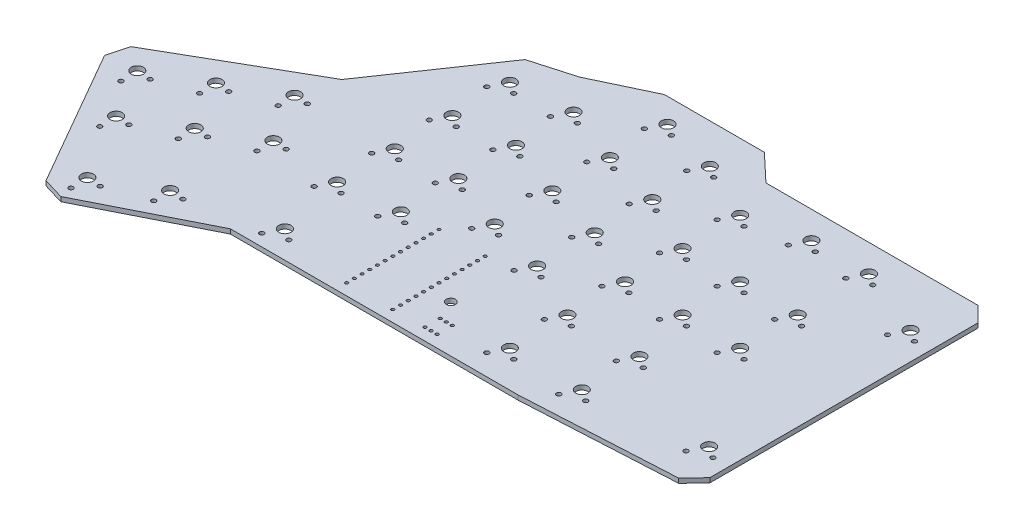
SolidWorks part; units mm, degrees
ref_plane "Front Plane" through (0, 0, 0) normal (0, 0, 1) x (1, 0, 0)
ref_plane "Top Plane" through (0, 0, 0) normal (0, 1, 0) x (1, 0, 0)
ref_plane "Right Plane" through (0, 0, 0) normal (1, 0, 0) x (0, 0, -1)
sketch "Main" plane through (0, 0, 0) normal (0, 1, 0) x (1, 0, 0)
  line L0 (6.46, 3.92) -> (12.81, 6.46) construction
  line L1 (0, 0) -> (18, 0) construction
  line L2 (0, 0) -> (0, 18) construction
  line L3 (0, 18) -> (18, 18) construction
  line L4 (18, 0) -> (18, 18) construction
  line L5 (2, 16) -> (16, 16)
  line L6 (2, 16) -> (2, 2)
  line L7 (2, 2) -> (16, 2)
  line L8 (16, 16) -> (16, 2)
  line L18 (9, 9) -> (6.46, 3.92) construction
  line L20 (9, 9) -> (12.81, 6.46) construction
  line L22 (25.46, 5.92) -> (31.81, 8.46) construction
  line L23 (19, 2) -> (37, 2) construction
  line L24 (19, 2) -> (19, 20) construction
  line L25 (19, 20) -> (37, 20) construction
  line L26 (37, 2) -> (37, 20) construction
  line L27 (21, 18) -> (35, 18)
  line L28 (21, 18) -> (21, 4)
  line L29 (21, 4) -> (35, 4)
  line L30 (35, 18) -> (35, 4)
  line L31 (28, 11) -> (25.46, 5.92) construction
  line L32 (28, 11) -> (31.81, 8.46) construction
  line L33 (44.46, 17.92) -> (50.81, 20.46) construction
  line L34 (38, 14) -> (56, 14) construction
  line L35 (38, 14) -> (38, 32) construction
  line L36 (38, 32) -> (56, 32) construction
  line L37 (56, 14) -> (56, 32) construction
  line L38 (40, 30) -> (54, 30)
  line L39 (40, 30) -> (40, 16)
  line L40 (40, 16) -> (54, 16)
  line L41 (54, 30) -> (54, 16)
  line L42 (47, 23) -> (44.46, 17.92) construction
  line L43 (47, 23) -> (50.81, 20.46) construction
  line L44 (63.46, 12.92) -> (69.81, 15.46) construction
  line L45 (57, 9) -> (75, 9) construction
  line L46 (57, 9) -> (57, 27) construction
  line L47 (57, 27) -> (75, 27) construction
  line L48 (75, 9) -> (75, 27) construction
  line L49 (59, 25) -> (73, 25)
  line L50 (59, 25) -> (59, 11)
  line L51 (59, 11) -> (73, 11)
  line L52 (73, 25) -> (73, 11)
  line L53 (66, 18) -> (63.46, 12.92) construction
  line L54 (66, 18) -> (69.81, 15.46) construction
  line L55 (82.46, 3.92) -> (88.81, 6.46) construction
  line L56 (76, 0) -> (94, 0) construction
  line L57 (76, 0) -> (76, 18) construction
  line L58 (76, 18) -> (94, 18) construction
  line L59 (94, 0) -> (94, 18) construction
  line L60 (78, 16) -> (92, 16)
  line L61 (78, 16) -> (78, 2)
  line L62 (78, 2) -> (92, 2)
  line L63 (92, 16) -> (92, 2)
  line L64 (85, 9) -> (82.46, 3.92) construction
  line L65 (85, 9) -> (88.81, 6.46) construction
  line L66 (101.46, -15.08) -> (107.81, -12.54) construction
  line L67 (95, -19) -> (113, -19) construction
  line L68 (95, -19) -> (95, -1) construction
  line L69 (95, -1) -> (113, -1) construction
  line L70 (113, -19) -> (113, -1) construction
  line L71 (97, -3) -> (111, -3)
  line L72 (97, -3) -> (97, -17)
  line L73 (97, -17) -> (111, -17)
  line L74 (111, -3) -> (111, -17)
  line L75 (104, -10) -> (101.46, -15.08) construction
  line L76 (104, -10) -> (107.81, -12.54) construction
  line L77 (120.46, -15.08) -> (126.81, -12.54) construction
  line L78 (114, -19) -> (132, -19) construction
  line L79 (114, -19) -> (114, -1) construction
  line L80 (114, -1) -> (132, -1) construction
  line L81 (132, -19) -> (132, -1) construction
  line L82 (116, -3) -> (130, -3)
  line L83 (116, -3) -> (116, -17)
  line L84 (116, -17) -> (130, -17)
  line L85 (130, -3) -> (130, -17)
  line L86 (123, -10) -> (120.46, -15.08) construction
  line L87 (123, -10) -> (126.81, -12.54) construction
  line L88 (2, -3) -> (16, -3)
  line L89 (2, -3) -> (2, -17)
  line L90 (2, -17) -> (16, -17)
  line L91 (16, -3) -> (16, -17)
  line L92 (21, -1) -> (35, -1)
  line L93 (21, -1) -> (21, -15)
  line L94 (21, -15) -> (35, -15)
  line L95 (35, -1) -> (35, -15)
  line L96 (40, 11) -> (54, 11)
  line L97 (40, 11) -> (40, -3)
  line L98 (40, -3) -> (54, -3)
  line L99 (54, 11) -> (54, -3)
  line L100 (59, 6) -> (73, 6)
  line L101 (59, 6) -> (59, -8)
  line L102 (59, -8) -> (73, -8)
  line L103 (73, 6) -> (73, -8)
  line L104 (78, -3) -> (92, -3)
  line L105 (78, -3) -> (78, -17)
  line L106 (78, -17) -> (92, -17)
  line L107 (92, -3) -> (92, -17)
  line L108 (97, -22) -> (111, -22)
  line L109 (97, -22) -> (97, -36)
  line L110 (97, -36) -> (111, -36)
  line L111 (111, -22) -> (111, -36)
  line L112 (116, -22) -> (130, -22)
  line L113 (116, -22) -> (116, -36)
  line L114 (116, -36) -> (130, -36)
  line L115 (130, -22) -> (130, -36)
  line L116 (6.46, -15.08) -> (12.81, -12.54) construction
  line L117 (0, -19) -> (18, -19) construction
  line L118 (0, -19) -> (0, -1) construction
  line L119 (0, -1) -> (18, -1) construction
  line L120 (18, -19) -> (18, -1) construction
  line L121 (9, -10) -> (6.46, -15.08) construction
  line L122 (9, -10) -> (12.81, -12.54) construction
  line L123 (25.46, -13.08) -> (31.81, -10.54) construction
  line L124 (19, -17) -> (37, -17) construction
  line L125 (19, -17) -> (19, 1) construction
  line L126 (19, 1) -> (37, 1) construction
  line L127 (37, -17) -> (37, 1) construction
  line L128 (28, -8) -> (25.46, -13.08) construction
  line L129 (28, -8) -> (31.81, -10.54) construction
  line L130 (44.46, -1.08) -> (50.81, 1.46) construction
  line L131 (38, -5) -> (56, -5) construction
  line L132 (38, -5) -> (38, 13) construction
  line L133 (38, 13) -> (56, 13) construction
  line L134 (56, -5) -> (56, 13) construction
  line L135 (47, 4) -> (44.46, -1.08) construction
  line L136 (47, 4) -> (50.81, 1.46) construction
  line L137 (63.46, -6.08) -> (69.81, -3.54) construction
  line L138 (57, -10) -> (75, -10) construction
  line L139 (57, -10) -> (57, 8) construction
  line L140 (57, 8) -> (75, 8) construction
  line L141 (75, -10) -> (75, 8) construction
  line L142 (66, -1) -> (63.46, -6.08) construction
  line L143 (66, -1) -> (69.81, -3.54) construction
  line L144 (82.46, -15.08) -> (88.81, -12.54) construction
  line L145 (76, -19) -> (94, -19) construction
  line L146 (76, -19) -> (76, -1) construction
  line L147 (76, -1) -> (94, -1) construction
  line L148 (94, -19) -> (94, -1) construction
  line L149 (85, -10) -> (82.46, -15.08) construction
  line L150 (85, -10) -> (88.81, -12.54) construction
  line L151 (101.46, -34.08) -> (107.81, -31.54) construction
  line L152 (95, -38) -> (113, -38) construction
  line L153 (95, -38) -> (95, -20) construction
  line L154 (95, -20) -> (113, -20) construction
  line L155 (113, -38) -> (113, -20) construction
  line L156 (104, -29) -> (101.46, -34.08) construction
  line L157 (104, -29) -> (107.81, -31.54) construction
  line L158 (120.46, -34.08) -> (126.81, -31.54) construction
  line L159 (114, -38) -> (132, -38) construction
  line L160 (114, -38) -> (114, -20) construction
  line L161 (114, -20) -> (132, -20) construction
  line L162 (132, -38) -> (132, -20) construction
  line L163 (123, -29) -> (120.46, -34.08) construction
  line L164 (123, -29) -> (126.81, -31.54) construction
  line L165 (2, -22) -> (16, -22)
  line L166 (2, -22) -> (2, -36)
  line L167 (2, -36) -> (16, -36)
  line L168 (16, -22) -> (16, -36)
  line L169 (21, -20) -> (35, -20)
  line L170 (21, -20) -> (21, -34)
  line L171 (21, -34) -> (35, -34)
  line L172 (35, -20) -> (35, -34)
  line L173 (40, -8) -> (54, -8)
  line L174 (40, -8) -> (40, -22)
  line L175 (40, -22) -> (54, -22)
  line L176 (54, -8) -> (54, -22)
  line L177 (59, -13) -> (73, -13)
  line L178 (59, -13) -> (59, -27)
  line L179 (59, -27) -> (73, -27)
  line L180 (73, -13) -> (73, -27)
  line L181 (78, -22) -> (92, -22)
  line L182 (78, -22) -> (78, -36)
  line L183 (78, -36) -> (92, -36)
  line L184 (92, -22) -> (92, -36)
  line L193 (6.46, -34.08) -> (12.81, -31.54) construction
  line L194 (0, -38) -> (18, -38) construction
  line L195 (0, -38) -> (0, -20) construction
  line L196 (0, -20) -> (18, -20) construction
  line L197 (18, -38) -> (18, -20) construction
  line L198 (9, -29) -> (6.46, -34.08) construction
  line L199 (9, -29) -> (12.81, -31.54) construction
  line L200 (25.46, -32.08) -> (31.81, -29.54) construction
  line L201 (19, -36) -> (37, -36) construction
  line L202 (19, -36) -> (19, -18) construction
  line L203 (19, -18) -> (37, -18) construction
  line L204 (37, -36) -> (37, -18) construction
  line L205 (28, -27) -> (25.46, -32.08) construction
  line L206 (28, -27) -> (31.81, -29.54) construction
  line L207 (44.46, -20.08) -> (50.81, -17.54) construction
  line L208 (38, -24) -> (56, -24) construction
  line L209 (38, -24) -> (38, -6) construction
  line L210 (38, -6) -> (56, -6) construction
  line L211 (56, -24) -> (56, -6) construction
  line L212 (47, -15) -> (44.46, -20.08) construction
  line L213 (47, -15) -> (50.81, -17.54) construction
  line L214 (63.46, -25.08) -> (69.81, -22.54) construction
  line L215 (57, -29) -> (75, -29) construction
  line L216 (57, -29) -> (57, -11) construction
  line L217 (57, -11) -> (75, -11) construction
  line L218 (75, -29) -> (75, -11) construction
  line L219 (66, -20) -> (63.46, -25.08) construction
  line L220 (66, -20) -> (69.81, -22.54) construction
  line L221 (82.46, -34.08) -> (88.81, -31.54) construction
  line L222 (76, -38) -> (94, -38) construction
  line L223 (76, -38) -> (76, -20) construction
  line L224 (76, -20) -> (94, -20) construction
  line L225 (94, -38) -> (94, -20) construction
  line L226 (85, -29) -> (82.46, -34.08) construction
  line L227 (85, -29) -> (88.81, -31.54) construction
  line L228 (97, 20.5) -> (111, 20.5)
  line L231 (97, 20.5) -> (97, 6.5)
  line L232 (97, 6.5) -> (111, 6.5)
  line L233 (111, 20.5) -> (111, 6.5)
  line L234 (116, 20.5) -> (130, 20.5)
  line L235 (116, 20.5) -> (116, 6.5)
  line L236 (116, 6.5) -> (130, 6.5)
  line L237 (130, 20.5) -> (130, 6.5)
  line L238 (101.46, 8.42) -> (107.81, 10.96) construction
  line L239 (95, 4.5) -> (113, 4.5) construction
  line L240 (95, 4.5) -> (95, 22.5) construction
  line L241 (95, 22.5) -> (113, 22.5) construction
  line L242 (2, -41) -> (16, -41)
  line L243 (2, -41) -> (2, -55)
  line L244 (2, -55) -> (16, -55)
  line L245 (16, -41) -> (16, -55)
  line L246 (21, -39) -> (35, -39)
  line L247 (21, -39) -> (21, -53)
  line L248 (21, -53) -> (35, -53)
  line L249 (35, -39) -> (35, -53)
  line L250 (40, -27) -> (54, -27)
  line L251 (40, -27) -> (40, -41)
  line L252 (40, -41) -> (54, -41)
  line L253 (54, -27) -> (54, -41)
  line L254 (59, -32) -> (73, -32)
  line L255 (59, -32) -> (59, -46)
  line L256 (59, -46) -> (73, -46)
  line L257 (73, -32) -> (73, -46)
  line L258 (78, -41) -> (92, -41)
  line L259 (78, -41) -> (78, -55)
  line L260 (78, -55) -> (92, -55)
  line L261 (92, -41) -> (92, -55)
  line L270 (6.46, -53.08) -> (12.81, -50.54) construction
  line L271 (0, -57) -> (18, -57) construction
  line L272 (0, -57) -> (0, -39) construction
  line L273 (0, -39) -> (18, -39) construction
  line L274 (18, -57) -> (18, -39) construction
  line L275 (9, -48) -> (6.46, -53.08) construction
  line L276 (9, -48) -> (12.81, -50.54) construction
  line L277 (25.46, -51.08) -> (31.81, -48.54) construction
  line L278 (19, -55) -> (37, -55) construction
  line L279 (19, -55) -> (19, -37) construction
  line L280 (19, -37) -> (37, -37) construction
  line L281 (37, -55) -> (37, -37) construction
  line L282 (28, -46) -> (25.46, -51.08) construction
  line L283 (28, -46) -> (31.81, -48.54) construction
  line L284 (44.46, -39.08) -> (50.81, -36.54) construction
  line L285 (38, -43) -> (56, -43) construction
  line L286 (38, -43) -> (38, -25) construction
  line L287 (38, -25) -> (56, -25) construction
  line L288 (56, -43) -> (56, -25) construction
  line L289 (47, -34) -> (44.46, -39.08) construction
  line L290 (47, -34) -> (50.81, -36.54) construction
  line L291 (63.46, -44.08) -> (69.81, -41.54) construction
  line L292 (57, -48) -> (75, -48) construction
  line L293 (57, -48) -> (57, -30) construction
  line L294 (57, -30) -> (75, -30) construction
  line L295 (75, -48) -> (75, -30) construction
  line L296 (66, -39) -> (63.46, -44.08) construction
  line L297 (66, -39) -> (69.81, -41.54) construction
  line L298 (82.46, -53.08) -> (88.81, -50.54) construction
  line L299 (76, -57) -> (94, -57) construction
  line L300 (76, -57) -> (76, -39) construction
  line L301 (76, -39) -> (94, -39) construction
  line L302 (94, -57) -> (94, -39) construction
  line L303 (85, -48) -> (82.46, -53.08) construction
  line L304 (85, -48) -> (88.81, -50.54) construction
  line L305 (113, 4.5) -> (113, 22.5) construction
  line L306 (104, 13.5) -> (101.46, 8.42) construction
  line L307 (104, 13.5) -> (107.81, 10.96) construction
  line L308 (120.46, 8.42) -> (126.81, 10.96) construction
  line L309 (114, 4.5) -> (132, 4.5) construction
  line L310 (114, 4.5) -> (114, 22.5) construction
  line L311 (114, 22.5) -> (132, 22.5) construction
  line L312 (132, 4.5) -> (132, 22.5) construction
  line L313 (123, 13.5) -> (120.46, 8.42) construction
  line L314 (123, 13.5) -> (126.81, 10.96) construction
  line L319 (97, -60) -> (111, -60)
  line L320 (97, -60) -> (97, -74)
  line L321 (97, -74) -> (111, -74)
  line L322 (111, -60) -> (111, -74)
  line L323 (116, -60) -> (130, -60)
  line L324 (116, -60) -> (116, -74)
  line L325 (116, -74) -> (130, -74)
  line L326 (130, -60) -> (130, -74)
  line L327 (101.46, -72.08) -> (107.81, -69.54) construction
  line L328 (95, -76) -> (113, -76) construction
  line L329 (95, -76) -> (95, -58) construction
  line L330 (95, -58) -> (113, -58) construction
  line L331 (113, -76) -> (113, -58) construction
  line L332 (104, -67) -> (101.46, -72.08) construction
  line L333 (104, -67) -> (107.81, -69.54) construction
  line L334 (120.46, -72.08) -> (126.81, -69.54) construction
  line L335 (114, -76) -> (132, -76) construction
  line L336 (114, -76) -> (114, -58) construction
  line L337 (114, -58) -> (132, -58) construction
  line L338 (132, -76) -> (132, -58) construction
  line L339 (123, -67) -> (120.46, -72.08) construction
  line L340 (123, -67) -> (126.81, -69.54) construction
  line L341 (97, -41) -> (111, -41)
  line L342 (97, -41) -> (97, -55)
  line L343 (97, -55) -> (111, -55)
  line L344 (111, -41) -> (111, -55)
  line L345 (116, -41) -> (130, -41)
  line L346 (116, -41) -> (116, -55)
  line L347 (116, -55) -> (130, -55)
  line L348 (130, -41) -> (130, -55)
  line L349 (101.46, -53.08) -> (107.81, -50.54) construction
  line L350 (95, -39) -> (113, -39) construction
  line L351 (113, -57) -> (113, -39) construction
  line L352 (104, -48) -> (101.46, -53.08) construction
  line L353 (104, -48) -> (107.81, -50.54) construction
  line L354 (120.46, -53.08) -> (126.81, -50.54) construction
  line L355 (114, -57) -> (132, -57) construction
  line L356 (114, -57) -> (114, -39) construction
  line L357 (114, -39) -> (132, -39) construction
  line L358 (132, -57) -> (132, -39) construction
  line L359 (123, -48) -> (120.46, -53.08) construction
  line L360 (123, -48) -> (126.81, -50.54) construction
  line L361 (95, -57) -> (113, -57) construction
  line L362 (95, -57) -> (95, -39) construction
  circle A0 centre (9, 9) radius 2 construction
  circle A1 centre (6.46, 3.92) radius 1.5 construction
  circle A2 centre (12.81, 6.46) radius 1.5 construction
  circle A6 centre (28, 11) radius 2 construction
  circle A7 centre (25.46, 5.92) radius 1.5 construction
  circle A8 centre (31.81, 8.46) radius 1.5 construction
  circle A9 centre (47, 23) radius 2 construction
  circle A10 centre (44.46, 17.92) radius 1.5 construction
  circle A11 centre (50.81, 20.46) radius 1.5 construction
  circle A12 centre (66, 18) radius 2 construction
  circle A13 centre (63.46, 12.92) radius 1.5 construction
  circle A14 centre (69.81, 15.46) radius 1.5 construction
  circle A15 centre (85, 9) radius 2 construction
  circle A16 centre (82.46, 3.92) radius 1.5 construction
  circle A17 centre (88.81, 6.46) radius 1.5 construction
  circle A18 centre (104, -10) radius 2 construction
  circle A19 centre (101.46, -15.08) radius 1.5 construction
  circle A20 centre (107.81, -12.54) radius 1.5 construction
  circle A21 centre (123, -10) radius 2 construction
  circle A22 centre (120.46, -15.08) radius 1.5 construction
  circle A23 centre (126.81, -12.54) radius 1.5 construction
  circle A24 centre (9, -10) radius 2 construction
  circle A25 centre (6.46, -15.08) radius 1.5 construction
  circle A26 centre (12.81, -12.54) radius 1.5 construction
  circle A27 centre (28, -8) radius 2 construction
  circle A28 centre (25.46, -13.08) radius 1.5 construction
  circle A29 centre (31.81, -10.54) radius 1.5 construction
  circle A30 centre (47, 4) radius 2 construction
  circle A31 centre (44.46, -1.08) radius 1.5 construction
  circle A32 centre (50.81, 1.46) radius 1.5 construction
  circle A33 centre (66, -1) radius 2 construction
  circle A34 centre (63.46, -6.08) radius 1.5 construction
  circle A35 centre (69.81, -3.54) radius 1.5 construction
  circle A36 centre (85, -10) radius 2 construction
  circle A37 centre (82.46, -15.08) radius 1.5 construction
  circle A38 centre (88.81, -12.54) radius 1.5 construction
  circle A39 centre (104, -29) radius 2 construction
  circle A40 centre (101.46, -34.08) radius 1.5 construction
  circle A41 centre (107.81, -31.54) radius 1.5 construction
  circle A42 centre (123, -29) radius 2 construction
  circle A43 centre (120.46, -34.08) radius 1.5 construction
  circle A44 centre (126.81, -31.54) radius 1.5 construction
  circle A45 centre (9, -29) radius 2 construction
  circle A46 centre (6.46, -34.08) radius 1.5 construction
  circle A47 centre (12.81, -31.54) radius 1.5 construction
  circle A48 centre (28, -27) radius 2 construction
  circle A49 centre (25.46, -32.08) radius 1.5 construction
  circle A50 centre (31.81, -29.54) radius 1.5 construction
  circle A51 centre (47, -15) radius 2 construction
  circle A52 centre (44.46, -20.08) radius 1.5 construction
  circle A53 centre (50.81, -17.54) radius 1.5 construction
  circle A54 centre (66, -20) radius 2 construction
  circle A55 centre (63.46, -25.08) radius 1.5 construction
  circle A56 centre (69.81, -22.54) radius 1.5 construction
  circle A57 centre (85, -29) radius 2 construction
  circle A58 centre (82.46, -34.08) radius 1.5 construction
  circle A59 centre (88.81, -31.54) radius 1.5 construction
  circle A60 centre (104, 13.5) radius 2 construction
  circle A61 centre (101.46, 8.42) radius 1.5 construction
  circle A62 centre (107.81, 10.96) radius 1.5 construction
  circle A63 centre (123, 13.5) radius 2 construction
  circle A64 centre (120.46, 8.42) radius 1.5 construction
  circle A65 centre (126.81, 10.96) radius 1.5 construction
  circle A66 centre (9, -48) radius 2 construction
  circle A67 centre (6.46, -53.08) radius 1.5 construction
  circle A68 centre (12.81, -50.54) radius 1.5 construction
  circle A69 centre (28, -46) radius 2 construction
  circle A70 centre (25.46, -51.08) radius 1.5 construction
  circle A71 centre (31.81, -48.54) radius 1.5 construction
  circle A72 centre (47, -34) radius 2 construction
  circle A73 centre (44.46, -39.08) radius 1.5 construction
  circle A74 centre (50.81, -36.54) radius 1.5 construction
  circle A75 centre (66, -39) radius 2 construction
  circle A76 centre (63.46, -44.08) radius 1.5 construction
  circle A77 centre (69.81, -41.54) radius 1.5 construction
  circle A78 centre (85, -48) radius 2 construction
  circle A79 centre (82.46, -53.08) radius 1.5 construction
  circle A80 centre (88.81, -50.54) radius 1.5 construction
  circle A87 centre (104, -67) radius 2 construction
  circle A88 centre (101.46, -72.08) radius 1.5 construction
  circle A89 centre (107.81, -69.54) radius 1.5 construction
  circle A90 centre (123, -67) radius 2 construction
  circle A91 centre (120.46, -72.08) radius 1.5 construction
  circle A92 centre (126.81, -69.54) radius 1.5 construction
  circle A93 centre (104, -48) radius 2 construction
  circle A94 centre (101.46, -53.08) radius 1.5 construction
  circle A95 centre (107.81, -50.54) radius 1.5 construction
  circle A96 centre (123, -48) radius 2 construction
  circle A97 centre (120.46, -53.08) radius 1.5 construction
  circle A98 centre (126.81, -50.54) radius 1.5 construction
  point P9 (9, 16)
  point P10 (9, 18)
  point P11 (2, 9)
  point P12 (0, 9)
  point P30 (28, 18)
  point P31 (28, 20)
  point P32 (21, 11)
  point P33 (19, 11)
  point P46 (47, 30)
  point P47 (47, 32)
  point P48 (40, 23)
  point P49 (38, 23)
  point P64 (66, 25)
  point P65 (66, 27)
  point P66 (59, 18)
  point P67 (57, 18)
  point P82 (85, 16)
  point P83 (85, 18)
  point P84 (78, 9)
  point P85 (76, 9)
  point P100 (104, -3)
  point P101 (104, -1)
  point P102 (97, -10)
  point P103 (95, -10)
  point P118 (123, -3)
  point P119 (123, -1)
  point P120 (116, -10)
  point P121 (114, -10)
  dimension "D6" = 4
  dimension "D7" = 3
  dimension "D10" = 1
  dimension "D11" = 5
  dimension "D1" = 18
  dimension "D2" = 14
  dimension "D3" = 3.81
  dimension "D4" = 2.54
  dimension "D5" = 2.54
  dimension "D8" = 1
  dimension "D9" = 12
  dimension "D12" = 1
  dimension "D13" = 2
  dimension "D14" = 1
  dimension "D15" = 9
  dimension "D16" = 1
  dimension "D17" = 5.08
  dimension "D18" = 1
  dimension "D20" = 1
  dimension "D22" = 4.5
  dimension "D23" = 2.54
  dimension "D24" = 2.54
  dimension "D25" = 2.54
  dimension "D26" = 2.54
  dimension "D27" = 2.54
  dimension "D28" = 2.54
  dimension "D19" = 4
  dimension "D21" = 2
sketch "EntBckSp" plane through (0, 0, 0) normal (0, 1, 0) x (1, 0, 0)
  line L0 (0, 0) -> (18, 0) construction
  line L1 (139, 11.25) -> (153, 11.25)
  line L2 (139, 11.25) -> (139, -2.75)
  line L3 (139, -2.75) -> (153, -2.75)
  line L4 (153, 11.25) -> (153, -2.75)
  line L5 (137, 18) -> (155, 18) construction
  line L6 (137, 18) -> (137, -9.5) construction
  line L7 (137, -9.5) -> (155, -9.5) construction
  line L8 (155, 18) -> (155, -9.5) construction
  line L9 (2, 2) -> (16, 2) construction
  line L10 (143.46, -0.83) -> (146, 4.25) construction
  line L11 (146, 4.25) -> (149.81, 1.71) construction
  line L12 (149.81, 1.71) -> (143.46, -0.83) construction
  line L13 (6.46, 3.92) -> (12.81, 6.46) construction
  line L14 (9, 9) -> (6.46, 3.92) construction
  line L15 (9, 9) -> (12.81, 6.46) construction
  line L16 (2, -55) -> (16, -55) construction
  line L17 (132, -19) -> (132, -1) construction
  line L18 (101.75, -41) -> (115.75, -41)
  line L19 (101.75, -41) -> (101.75, -55)
  line L20 (101.75, -55) -> (115.75, -55)
  line L21 (115.75, -41) -> (115.75, -55)
  line L22 (95, -39) -> (122.5, -39) construction
  line L23 (95, -39) -> (95, -57) construction
  line L24 (95, -57) -> (122.5, -57) construction
  line L25 (122.5, -39) -> (122.5, -57) construction
  line L26 (106.21, -53.08) -> (108.75, -48) construction
  line L27 (108.75, -48) -> (112.56, -50.54) construction
  line L28 (112.56, -50.54) -> (106.21, -53.08) construction
  line L29 (0, 18) -> (18, 18) construction
  line L30 (46.5, -79) -> (28.5, -79) construction
  line L31 (101.75, -60) -> (115.75, -60)
  line L32 (101.75, -60) -> (101.75, -74)
  line L33 (101.75, -74) -> (115.75, -74)
  line L34 (115.75, -60) -> (115.75, -74)
  line L35 (95, -58) -> (122.5, -58) construction
  line L36 (95, -58) -> (95, -76) construction
  line L37 (95, -76) -> (122.5, -76) construction
  line L38 (122.5, -58) -> (122.5, -76) construction
  line L39 (106.21, -72.08) -> (108.75, -67) construction
  line L40 (108.75, -67) -> (112.56, -69.54) construction
  line L41 (112.56, -69.54) -> (106.21, -72.08) construction
  line L42 (139, -55.25) -> (153, -55.25)
  line L43 (139, -55.25) -> (139, -69.25)
  line L44 (139, -69.25) -> (153, -69.25)
  line L45 (153, -55.25) -> (153, -69.25)
  line L46 (137, -48.5) -> (155, -48.5) construction
  line L47 (137, -48.5) -> (137, -76) construction
  line L48 (137, -76) -> (155, -76) construction
  line L49 (155, -48.5) -> (155, -76) construction
  line L50 (143.46, -67.33) -> (146, -62.25) construction
  line L51 (146, -62.25) -> (149.81, -64.79) construction
  line L52 (149.81, -64.79) -> (143.46, -67.33) construction
  line L64 (95, -38) -> (95, -20) construction
  line L65 (114, -38) -> (132, -38) construction
  line L66 (6.75, -63) -> (20.75, -63)
  line L67 (6.75, -63) -> (6.75, -77)
  line L68 (6.75, -77) -> (20.75, -77)
  line L69 (20.75, -63) -> (20.75, -77)
  line L70 (0, -61) -> (27.5, -61) construction
  line L71 (0, -61) -> (0, -79) construction
  line L72 (0, -79) -> (27.5, -79) construction
  line L73 (27.5, -61) -> (27.5, -79) construction
  line L74 (11.21, -75.08) -> (13.75, -70) construction
  line L75 (13.75, -70) -> (17.56, -72.54) construction
  line L76 (17.56, -72.54) -> (11.21, -75.08) construction
  line L77 (94, -76) -> (76, -76) construction
  line L78 (0, -57) -> (0, -39) construction
  line L79 (78, -60) -> (92, -60)
  line L80 (30.5, -63) -> (44.5, -63) construction
  line L81 (30.5, -63) -> (30.5, -77) construction
  line L82 (30.5, -77) -> (44.5, -77) construction
  line L83 (44.5, -63) -> (44.5, -77) construction
  line L86 (34.96, -75.08) -> (37.5, -70) construction
  line L87 (37.5, -70) -> (41.31, -72.54) construction
  line L88 (41.31, -72.54) -> (34.96, -75.08) construction
  line L91 (51.25, -61) -> (51.25, -79) construction
  line L92 (23.75, -61) -> (23.75, -79) construction
  line L93 (46.5, -79) -> (46.5, -61) construction
  line L94 (46.5, -61) -> (28.5, -61) construction
  line L95 (28.5, -79) -> (28.5, -61) construction
  line L96 (78, -60) -> (78, -74)
  line L97 (78, -74) -> (92, -74)
  line L98 (92, -60) -> (92, -74)
  line L99 (82.46, -72.08) -> (85, -67) construction
  line L100 (85, -67) -> (88.81, -69.54) construction
  line L101 (88.81, -69.54) -> (82.46, -72.08) construction
  line L102 (94, -76) -> (94, -58) construction
  line L103 (94, -58) -> (76, -58) construction
  line L104 (76, -76) -> (76, -58) construction
  line L105 (78, -41) -> (92, -41) construction
  line L106 (76, -57) -> (94, -57) construction
  line L107 (85, -48) -> (88.81, -50.54) construction
  line L108 (85, -48) -> (82.46, -53.08) construction
  line L109 (82.46, -53.08) -> (88.81, -50.54) construction
  circle A0 centre (146, 4.25) radius 2 construction
  circle A1 centre (143.46, -0.83) radius 1.5 construction
  circle A2 centre (149.81, 1.71) radius 1.5 construction
  circle A3 centre (9, 9) radius 2 construction
  circle A4 centre (6.46, 3.92) radius 1.5 construction
  circle A5 centre (108.75, -48) radius 2 construction
  circle A6 centre (106.21, -53.08) radius 1.5 construction
  circle A7 centre (112.56, -50.54) radius 1.5 construction
  circle A8 centre (108.75, -67) radius 2 construction
  circle A9 centre (106.21, -72.08) radius 1.5 construction
  circle A10 centre (112.56, -69.54) radius 1.5 construction
  circle A11 centre (146, -62.25) radius 2 construction
  circle A12 centre (143.46, -67.33) radius 1.5 construction
  circle A13 centre (149.81, -64.79) radius 1.5 construction
  circle A17 centre (13.75, -70) radius 2 construction
  circle A18 centre (11.21, -75.08) radius 1.5 construction
  circle A19 centre (17.56, -72.54) radius 1.5 construction
  circle A20 centre (37.5, -70) radius 2 construction
  circle A21 centre (34.96, -75.08) radius 1.5 construction
  circle A22 centre (41.31, -72.54) radius 1.5 construction
  circle A23 centre (85, -67) radius 2 construction
  circle A24 centre (82.46, -72.08) radius 1.5 construction
  circle A25 centre (88.81, -69.54) radius 1.5 construction
  circle A26 centre (85, -48) radius 2 construction
  circle A27 centre (88.81, -50.54) radius 1.5 construction
  point P14 (146, 11.25)
  point P15 (146, 18)
  point P16 (139, 4.25)
  point P17 (137, 4.25)
  point P51 (108.75, -41)
  point P52 (108.75, -39)
  point P53 (101.75, -48)
  point P54 (95, -48)
  point P87 (146, -55.25)
  point P88 (146, -48.5)
  point P89 (139, -62.25)
  point P90 (137, -62.25)
  point P105 (13.75, -63)
  point P106 (13.75, -61)
  point P107 (6.75, -70)
  point P108 (0, -70)
  point P109 (37.5, -63)
  point P117 (85, -60)
  point P132 (37.5, -61)
  point P147 (85, -58)
  point P150 (0, 0)
  point P163 (0, 0)
  point P164 (0, 0)
  point P165 (78, -67)
  point P166 (0, 0)
  point P167 (84.9312, -67.3351)
  point P168 (93.2373, -76)
  point P169 (84.9697, -66.5227)
  point P171 (0, 0)
  dimension "D1" = 27.5
  dimension "D2" = 5
  dimension "D3" = 1
  dimension "D5" = 1
  dimension "D6" = 2
  dimension "D7" = 1
  dimension "D8" = 8
  dimension "D9" = 2.54
  dimension "D10" = 2.54
  dimension "D11" = 2.54
  dimension "D12" = 2.54
  dimension "D4" = 2
sketch "MoLng" plane through (0, 0, 0) normal (0, 1, 0) x (1, 0, 0)
  line L0 (-25.7133, -75.4047) -> (-13.5763, -68.4267)
  line L1 (-25.7133, -75.4047) -> (-18.7353, -87.5417)
  line L2 (-13.5763, -68.4267) -> (-6.5983, -80.5637)
  line L3 (-18.7353, -87.5417) -> (-6.5983, -80.5637)
  line L4 (-30.8116, -70.5498) -> (-15.2068, -61.578) construction
  line L5 (-30.8116, -70.5498) -> (-17.1047, -94.3903) construction
  line L6 (-15.2068, -61.578) -> (-1.5, -85.4186) construction
  line L7 (-17.1047, -94.3903) -> (-1.5, -85.4186) construction
  line L8 (-15.2068, -61.578) -> (-17.1047, -94.3903) construction
  line L9 (-25.7133, -75.4047) -> (-6.5983, -80.5637) construction
  line L10 (0, -61) -> (0, -79) construction
  line L11 (0, -79) -> (27.5, -79) construction
  line L12 (6.75, -77) -> (20.75, -77) construction
  line L13 (-16.1558, -77.9842) -> (13.75, -130) construction
  line L14 (-15.8972, -83.6579) -> (-11.5909, -78.3447) construction
  line L15 (-11.5909, -78.3447) -> (-16.1558, -77.9842) construction
  line L16 (-16.1558, -77.9842) -> (-15.8972, -83.6579) construction
  line L17 (17.56, -72.54) -> (11.21, -75.08) construction
  line L18 (11.21, -75.08) -> (13.75, -70) construction
  line L19 (13.75, -70) -> (17.56, -72.54) construction
  line L20 (-43.0519, -85.3733) -> (-30.9149, -78.3953)
  line L21 (-43.0519, -85.3733) -> (-36.0739, -97.5103)
  line L22 (-30.9149, -78.3953) -> (-23.9369, -90.5323)
  line L23 (-36.0739, -97.5103) -> (-23.9369, -90.5323)
  line L24 (-48.1502, -80.5184) -> (-32.5454, -71.5466) construction
  line L25 (-48.1502, -80.5184) -> (-34.4433, -104.3589) construction
  line L26 (-32.5454, -71.5466) -> (-18.8386, -95.3872) construction
  line L27 (-34.4433, -104.3589) -> (-18.8386, -95.3872) construction
  line L28 (-32.5454, -71.5466) -> (-34.4433, -104.3589) construction
  line L29 (-43.0519, -85.3733) -> (-23.9369, -90.5323) construction
  line L31 (-33.2358, -93.6265) -> (-28.9295, -88.3133) construction
  line L32 (-28.9295, -88.3133) -> (-33.4944, -87.9528) construction
  line L33 (-33.4944, -87.9528) -> (-33.2358, -93.6265) construction
  line L38 (-48.9084, -75.1869) -> (-55.8865, -63.0498)
  line L39 (-48.9084, -75.1869) -> (-36.7714, -68.2088)
  line L43 (-55.8865, -63.0498) -> (-43.7494, -56.0718)
  line L51 (-36.7714, -68.2088) -> (-43.7494, -56.0718)
  line L52 (-48.9084, -75.1869) -> (-43.7494, -56.0718) construction
  line L56 (-55.8865, -63.0498) -> (-36.7714, -68.2088) construction
  line L57 (2, -55) -> (16, -55) construction
  line L58 (-46.0703, -71.3031) -> (-41.7641, -65.9898) construction
  line L59 (-41.7641, -65.9898) -> (-46.3289, -65.6293) construction
  line L66 (-46.3289, -65.6293) -> (-46.0703, -71.3031) construction
  line L69 (9, -48) -> (12.81, -50.54) construction
  line L70 (6.46, -53.08) -> (12.81, -50.54) construction
  line L71 (9, -48) -> (6.46, -53.08) construction
  line L73 (-49.6455, -77.9176) -> (-58.6172, -62.3128) construction
  line L104 (-49.6455, -77.9176) -> (-34.0407, -68.9458) construction
  line L134 (-58.6172, -62.3128) -> (-43.0124, -53.3411) construction
  line L135 (-34.0407, -68.9458) -> (-43.0124, -53.3411) construction
  line L136 (-49.6455, -77.9176) -> (-43.0124, -53.3411) construction
  line L137 (-58.6172, -62.3128) -> (-34.0407, -68.9458) construction
  line L158 (0, -57) -> (18, -57) construction
  line L162 (-32.4368, -65.7167) -> (-39.4148, -53.5797)
  line L163 (-32.4368, -65.7167) -> (-20.2998, -58.7387)
  line L170 (-39.4148, -53.5797) -> (-27.2778, -46.6017)
  line L171 (-20.2998, -58.7387) -> (-27.2778, -46.6017)
  line L174 (-32.4368, -65.7167) -> (-27.2778, -46.6017) construction
  line L175 (-39.4148, -53.5797) -> (-20.2998, -58.7387) construction
  line L176 (-29.5987, -61.8329) -> (-25.2924, -56.5197) construction
  line L177 (-25.2924, -56.5197) -> (-29.8573, -56.1592) construction
  line L180 (-29.8573, -56.1592) -> (-29.5987, -61.8329) construction
  line L181 (-33.1738, -68.4474) -> (-42.1455, -52.8427) construction
  line L182 (-33.1738, -68.4474) -> (-17.569, -59.4757) construction
  line L183 (-42.1455, -52.8427) -> (-26.5408, -43.8709) construction
  line L184 (-17.569, -59.4757) -> (-26.5408, -43.8709) construction
  line L185 (-33.1738, -68.4474) -> (-26.5408, -43.8709) construction
  line L190 (-42.1455, -52.8427) -> (-17.569, -59.4757) construction
  line L191 (-15.9651, -56.2465) -> (-22.9431, -44.1095)
  line L192 (-15.9651, -56.2465) -> (-3.8281, -49.2685)
  line L193 (-22.9431, -44.1095) -> (-10.8061, -37.1315)
  line L194 (-3.8281, -49.2685) -> (-10.8061, -37.1315)
  line L195 (-15.9651, -56.2465) -> (-10.8061, -37.1315) construction
  line L196 (-22.9431, -44.1095) -> (-3.8281, -49.2685) construction
  line L197 (-13.127, -52.3627) -> (-8.8208, -47.0495) construction
  line L198 (-8.8208, -47.0495) -> (-13.3856, -46.689) construction
  line L199 (-13.3856, -46.689) -> (-13.127, -52.3627) construction
  line L200 (-16.7021, -58.9772) -> (-25.6738, -43.3725) construction
  line L201 (-16.7021, -58.9772) -> (-1.0974, -50.0055) construction
  line L202 (-25.6738, -43.3725) -> (-10.0691, -34.4008) construction
  line L203 (-1.0974, -50.0055) -> (-10.0691, -34.4008) construction
  line L204 (-16.7021, -58.9772) -> (-10.0691, -34.4008) construction
  line L205 (-25.6738, -43.3725) -> (-1.0974, -50.0055) construction
  line L206 (-41.9069, -49.245) -> (-48.885, -37.108)
  line L207 (-41.9069, -49.245) -> (-29.7699, -42.267)
  line L208 (-48.885, -37.108) -> (-36.7479, -30.13)
  line L209 (-29.7699, -42.267) -> (-36.7479, -30.13)
  line L210 (-41.9069, -49.245) -> (-36.7479, -30.13) construction
  line L211 (-48.885, -37.108) -> (-29.7699, -42.267) construction
  line L212 (-39.0688, -45.3612) -> (-34.7626, -40.048) construction
  line L213 (-34.7626, -40.048) -> (-39.3274, -39.6875) construction
  line L214 (-39.3274, -39.6875) -> (-39.0688, -45.3612) construction
  line L215 (-42.6439, -51.9757) -> (-51.6157, -36.371) construction
  line L216 (-42.6439, -51.9757) -> (-27.0392, -43.004) construction
  line L217 (-51.6157, -36.371) -> (-36.0109, -27.3993) construction
  line L218 (-27.0392, -43.004) -> (-36.0109, -27.3993) construction
  line L219 (-42.6439, -51.9757) -> (-36.0109, -27.3993) construction
  line L220 (-51.6157, -36.371) -> (-27.0392, -43.004) construction
  line L221 (-25.4353, -39.7749) -> (-32.4133, -27.6378)
  line L222 (-25.4353, -39.7749) -> (-13.2982, -32.7968)
  line L223 (-32.4133, -27.6378) -> (-20.2763, -20.6598)
  line L224 (-13.2982, -32.7968) -> (-20.2763, -20.6598)
  line L225 (-25.4353, -39.7749) -> (-20.2763, -20.6598) construction
  line L226 (-32.4133, -27.6378) -> (-13.2982, -32.7968) construction
  line L227 (-22.5972, -35.8911) -> (-18.2909, -30.5778) construction
  line L228 (-18.2909, -30.5778) -> (-22.8558, -30.2173) construction
  line L229 (-22.8558, -30.2173) -> (-22.5972, -35.8911) construction
  line L230 (-26.1723, -42.5056) -> (-35.144, -26.9008) construction
  line L231 (-26.1723, -42.5056) -> (-10.5675, -33.5338) construction
  line L232 (-35.144, -26.9008) -> (-19.5393, -17.9291) construction
  line L233 (-10.5675, -33.5338) -> (-19.5393, -17.9291) construction
  line L234 (-26.1723, -42.5056) -> (-19.5393, -17.9291) construction
  line L235 (-35.144, -26.9008) -> (-10.5675, -33.5338) construction
  line L236 (-58.3786, -58.7152) -> (-65.3566, -46.5782)
  line L237 (-58.3786, -58.7152) -> (-46.2416, -51.7372)
  line L238 (-65.3566, -46.5782) -> (-53.2196, -39.6001)
  line L239 (-46.2416, -51.7372) -> (-53.2196, -39.6001)
  line L240 (-58.3786, -58.7152) -> (-53.2196, -39.6001) construction
  line L241 (-65.3566, -46.5782) -> (-46.2416, -51.7372) construction
  line L242 (-55.5405, -54.8314) -> (-51.2343, -49.5181) construction
  line L243 (-51.2343, -49.5181) -> (-55.7991, -49.1577) construction
  line L244 (-55.7991, -49.1577) -> (-55.5405, -54.8314) construction
  line L245 (-59.1156, -61.4459) -> (-68.0873, -45.8412) construction
  line L246 (-59.1156, -61.4459) -> (-43.5109, -52.4742) construction
  line L247 (-68.0873, -45.8412) -> (-52.4826, -36.8694) construction
  line L248 (-43.5109, -52.4742) -> (-52.4826, -36.8694) construction
  line L249 (-59.1156, -61.4459) -> (-52.4826, -36.8694) construction
  line L250 (-68.0873, -45.8412) -> (-43.5109, -52.4742) construction
  circle A0 centre (13.75, -130) radius 60 construction
  circle A1 centre (-16.1558, -77.9842) radius 2 construction
  circle A2 centre (13.75, -70) radius 2 construction
  circle A3 centre (-15.8972, -83.6579) radius 1.5 construction
  circle A4 centre (-11.5909, -78.3447) radius 1.5 construction
  circle A5 centre (11.21, -75.08) radius 1.5 construction
  circle A6 centre (-33.4944, -87.9528) radius 2 construction
  circle A7 centre (-33.2358, -93.6265) radius 1.5 construction
  circle A8 centre (-28.9295, -88.3133) radius 1.5 construction
  circle A12 centre (-46.3289, -65.6293) radius 2 construction
  circle A13 centre (-46.0703, -71.3031) radius 1.5 construction
  circle A14 centre (-41.7641, -65.9898) radius 1.5 construction
  circle A15 centre (6.46, -53.08) radius 1.5 construction
  circle A16 centre (9, -48) radius 2 construction
  circle A17 centre (-29.8573, -56.1592) radius 2 construction
  circle A18 centre (-25.2924, -56.5197) radius 1.5 construction
  circle A19 centre (-29.5987, -61.8329) radius 1.5 construction
  circle A20 centre (-13.3856, -46.689) radius 2 construction
  circle A24 centre (-8.8208, -47.0495) radius 1.5 construction
  circle A25 centre (-13.127, -52.3627) radius 1.5 construction
  circle A26 centre (-39.3274, -39.6875) radius 2 construction
  circle A27 centre (-34.7626, -40.048) radius 1.5 construction
  circle A28 centre (-39.0688, -45.3612) radius 1.5 construction
  circle A29 centre (-22.8558, -30.2173) radius 2 construction
  circle A30 centre (-18.2909, -30.5778) radius 1.5 construction
  circle A31 centre (-22.5972, -35.8911) radius 1.5 construction
  circle A32 centre (-55.7991, -49.1577) radius 2 construction
  circle A35 centre (-51.2343, -49.5181) radius 1.5 construction
  circle A36 centre (-55.5405, -54.8314) radius 1.5 construction
  point P2 (-16.1558, -77.9842)
  point P11 (-16.1558, -77.9842)
  point P28 (-46.3289, -65.6293)
  point P39 (-33.4944, -87.9528)
  point P46 (-33.4944, -87.9528)
  point P89 (-29.8573, -56.1592)
  point P112 (-13.3856, -46.689)
  point P134 (-39.3274, -39.6875)
  point P155 (-22.8558, -30.2173)
  point P170 (-55.7991, -49.1577)
  dimension "D1" = 120
  dimension "D2" = 2
  dimension "D4" = 2
  dimension "D5" = 3
  dimension "D6" = 1.5
  dimension "D8" = 1
  dimension "D10" = 21.08
  dimension "D11" = 21.08
  dimension "D9" = 21.08
  dimension "D3" = 3
  dimension "D7" = 1
sketch "Sketch2" plane through (0, 0, 0) normal (0, 1, 0) x (1, 0, 0)
  line L0 (71, 31) -> (38, 31)
  line L1 (38, 31) -> (19, 22)
  line L2 (19, 22) -> (5, 18)
  line L3 (5, 18) -> (-19.5393, -17.9291)
  line L4 (-19.5393, -17.9291) -> (-63.7527, -43.349)
  line L5 (-65.5952, -50.1758) -> (-39.4446, -95.6601)
  line L7 (-32.4762, -97.7489) -> (4.75, -79)
  line L8 (4.75, -79) -> (99.75, -79)
  line L9 (99.75, -79) -> (155, -76) construction
  line L10 (155, -76) -> (155, 22.5) construction
  line L11 (155, 22.5) -> (80, 22.5) construction
  line L12 (80, 22.5) -> (71, 31)
  line L13 (6.75, -63) -> (6.75, -77) construction
  line L14 (38, 32) -> (56, 32) construction
  line L15 (150, 22.5) -> (155, 17.5)
  line L17 (0, 18) -> (18, 18) construction
  line L18 (-63.7527, -43.349) -> (-65.5952, -50.1758)
  line L19 (155, -71) -> (150, -76.2715)
  line L20 (-68.0873, -45.8412) -> (-52.4826, -36.8694) construction
  line L21 (-59.1156, -61.4459) -> (-68.0873, -45.8412) construction
  line L22 (95, -76) -> (122.5, -76) construction
  line L23 (155, -48.5) -> (155, -76) construction
  line L24 (114, 22.5) -> (132, 22.5) construction
  line L25 (0, -79) -> (27.5, -79) construction
  line L26 (101.75, -60) -> (101.75, -74) construction
  line L27 (75, 9) -> (75, 27) construction
  line L28 (38, 14) -> (38, 32) construction
  line L29 (19, 2) -> (19, 20) construction
  line L30 (19, 20) -> (37, 20) construction
  line L31 (80, 22.5) -> (150, 22.5)
  line L32 (155, 17.5) -> (155, -71)
  line L33 (99.75, -79) -> (150, -76.2715)
  line L34 (-39.4446, -95.6601) -> (-32.4762, -97.7489)
  line L35 (-36.0739, -97.5103) -> (-23.9369, -90.5323) construction
  line L36 (-48.1502, -80.5184) -> (-34.4433, -104.3589) construction
  dimension "D1" = 2
  dimension "D3" = 5
  dimension "D4" = 95
  dimension "D5" = 5
  dimension "D6" = 50.324
  dimension "D7" = 88.5
  dimension "D8" = 5
  dimension "D9" = 70
  dimension "D10" = 12.3794
  dimension "D11" = 1
  dimension "D12" = 2
  dimension "D13" = 21.0238
  dimension "D14" = 14.5602
  dimension "D15" = 43.5095
  dimension "D16" = 5
  dimension "D17" = 5
  dimension "D18" = 5
  dimension "D19" = 2
  dimension "D20" = 51
  dimension "D21" = 4
  dimension "D22" = 2
  dimension "D23" = 33
  dimension "D24" = 5
  dimension "D25" = 5
  dimension "D26" = 5
  dimension "D27" = 5
  dimension "D28" = 52.466
  dimension "D29" = 41.6811
extrude "Main_plate" add sketch "Sketch2" against normal blind 1.5
sketch "Sketch3" plane through (0, 0, 0) normal (0, 1, 0) x (1, 0, 0)
  line L0 (-32.4133, -27.6378) -> (-13.2982, -32.7968) construction
  line L1 (-48.9084, -75.1869) -> (-43.7494, -56.0718) construction
  line L2 (-32.5454, -71.5466) -> (-34.4433, -104.3589) construction
  circle A0 centre (-55.7991, -49.1577) radius 2
  circle A1 centre (-39.3274, -39.6875) radius 2
  circle A2 centre (-22.8558, -30.2173) radius 2
  circle A3 centre (-46.3289, -65.6293) radius 2
  circle A4 centre (-29.8573, -56.1592) radius 2
  circle A5 centre (-13.3856, -46.689) radius 2
  circle A6 centre (-33.4944, -87.9528) radius 2
  circle A7 centre (-16.1558, -77.9842) radius 2
  circle A8 centre (13.75, -70) radius 2
  circle A10 centre (28, -46) radius 2
  circle A11 centre (9, -48) radius 2
  circle A12 centre (9, -29) radius 2
  circle A13 centre (28, -27) radius 2
  circle A14 centre (47, -34) radius 2
  circle A15 centre (66, -39) radius 2
  circle A16 centre (9, -10) radius 2
  circle A17 centre (9, 9) radius 2
  circle A18 centre (28, 11) radius 2
  circle A19 centre (47, 23) radius 2
  circle A20 centre (47, 4) radius 2
  circle A21 centre (28, -8) radius 2
  circle A22 centre (47, -15) radius 2
  circle A23 centre (66, 18) radius 2
  circle A24 centre (66, -1) radius 2
  circle A25 centre (66, -20) radius 2
  circle A26 centre (85, 9) radius 2
  circle A27 centre (104, 13.5) radius 2
  circle A28 centre (123, 13.5) radius 2
  circle A29 centre (146, 4.25) radius 2
  circle A30 centre (123, -10) radius 2
  circle A31 centre (104, -10) radius 2
  circle A32 centre (85, -10) radius 2
  circle A33 centre (85, -29) radius 2
  circle A34 centre (104, -29) radius 2
  circle A35 centre (123, -29) radius 2
  circle A36 centre (85, -48) radius 2
  circle A37 centre (108.75, -48) radius 2
  circle A38 centre (108.75, -67) radius 2
  circle A39 centre (146, -62.25) radius 2
  circle A40 centre (146, 4.25) radius 2 construction
  circle A41 centre (85, -67) radius 2
extrude "Switch_holes_main" cut sketch "Sketch3" against normal through all
sketch "Sketch4" plane through (0, 0, 0) normal (0, 1, 0) x (1, 0, 0)
  circle A0 centre (-55.5405, -54.8314) radius 0.75
  circle A1 centre (-51.2343, -49.5181) radius 0.75
  circle A2 centre (-39.0688, -45.3612) radius 0.75
  circle A3 centre (-34.7626, -40.048) radius 0.75
  circle A4 centre (-22.5972, -35.8911) radius 0.75
  circle A5 centre (-18.2909, -30.5778) radius 0.75
  circle A6 centre (25.46, -51.08) radius 0.75
  circle A7 centre (149.81, 1.71) radius 0.75
  circle A8 centre (143.46, -0.83) radius 0.75
  circle A9 centre (88.81, -69.54) radius 0.75
  circle A10 centre (120.46, 8.42) radius 0.75
  circle A11 centre (126.81, 10.96) radius 0.75
  circle A12 centre (126.81, -12.54) radius 0.75
  circle A13 centre (120.46, -15.08) radius 0.75
  circle A14 centre (143.46, -67.33) radius 0.75
  circle A15 centre (149.81, -64.79) radius 0.75
  circle A16 centre (126.81, -31.54) radius 0.75
  circle A17 centre (120.46, -34.08) radius 0.75
  circle A18 centre (107.81, -31.54) radius 0.75
  circle A19 centre (101.46, -34.08) radius 0.75
  circle A20 centre (106.21, -53.08) radius 0.75
  circle A21 centre (112.56, -50.54) radius 0.75
  circle A22 centre (112.56, -69.54) radius 0.75
  circle A23 centre (106.21, -72.08) radius 0.75
  circle A24 centre (107.81, 10.96) radius 0.75
  circle A25 centre (101.46, 8.42) radius 0.75
  circle A26 centre (107.81, -12.54) radius 0.75
  circle A27 centre (101.46, -15.08) radius 0.75
  circle A28 centre (88.81, -12.54) radius 0.75
  circle A29 centre (82.46, -15.08) radius 0.75
  circle A30 centre (82.46, 3.92) radius 0.75
  circle A31 centre (88.81, 6.46) radius 0.75
  circle A32 centre (88.81, -31.54) radius 0.75
  circle A33 centre (82.46, -34.08) radius 0.75
  circle A34 centre (69.81, 15.46) radius 0.75
  circle A35 centre (63.46, 12.92) radius 0.75
  circle A36 centre (69.81, -3.54) radius 0.75
  circle A37 centre (63.46, -6.08) radius 0.75
  circle A38 centre (69.81, -22.54) radius 0.75
  circle A39 centre (63.46, -25.08) radius 0.75
  circle A40 centre (63.46, -44.08) radius 0.75
  circle A41 centre (69.81, -41.54) radius 0.75
  circle A42 centre (88.81, -50.54) radius 0.75
  circle A43 centre (82.46, -53.08) radius 0.75
  circle A46 centre (31.81, -48.54) radius 0.75
  circle A47 centre (44.46, -39.08) radius 0.75
  circle A48 centre (50.81, -36.54) radius 0.75
  circle A49 centre (44.46, -20.08) radius 0.75
  circle A50 centre (50.81, -17.54) radius 0.75
  circle A51 centre (31.81, -29.54) radius 0.75
  circle A52 centre (25.46, -32.08) radius 0.75
  circle A53 centre (25.46, -13.08) radius 0.75
  circle A54 centre (31.81, -10.54) radius 0.75
  circle A55 centre (12.81, -12.54) radius 0.75
  circle A56 centre (6.46, -15.08) radius 0.75
  circle A57 centre (6.46, 3.92) radius 0.75
  circle A58 centre (12.81, 6.46) radius 0.75
  circle A59 centre (25.46, 5.92) radius 0.75
  circle A60 centre (31.81, 8.46) radius 0.75
  circle A61 centre (44.46, 17.92) radius 0.75
  circle A62 centre (50.81, 20.46) radius 0.75
  circle A63 centre (50.81, 1.46) radius 0.75
  circle A64 centre (44.46, -1.08) radius 0.75
  circle A65 centre (12.81, -31.54) radius 0.75
  circle A66 centre (6.46, -34.08) radius 0.75
  circle A67 centre (12.81, -50.54) radius 0.75
  circle A68 centre (6.46, -53.08) radius 0.75
  circle A69 centre (17.56, -72.54) radius 0.75
  circle A70 centre (11.21, -75.08) radius 0.75
  circle A71 centre (-8.8208, -47.0495) radius 0.75
  circle A72 centre (-13.127, -52.3627) radius 0.75
  circle A73 centre (-25.2924, -56.5197) radius 0.75
  circle A74 centre (-29.5987, -61.8329) radius 0.75
  circle A75 centre (-41.7641, -65.9898) radius 0.75
  circle A76 centre (-46.0703, -71.3031) radius 0.75
  circle A77 centre (-28.9295, -88.3133) radius 0.75
  circle A78 centre (-33.2358, -93.6265) radius 0.75
  circle A79 centre (-15.8972, -83.6579) radius 0.75
  circle A80 centre (-11.5909, -78.3447) radius 0.75
  circle A81 centre (82.46, -72.08) radius 0.75
  dimension "D1" = 1.5
extrude "Switch_holes" cut sketch "Sketch4" against normal through all
sketch "Sketch5" plane through (0, 0, 0) normal (0, 1, 0) x (1, 0, 0)
  line L0 (47, -34) -> (47, -79) construction
  line L1 (4.75, -79) -> (99.75, -79) construction
  line L2 (4.75, -79) -> (99.75, -79) construction
  circle A0 centre (39.38, -75.25) radius 0.5
  circle A1 centre (39.38, -72.71) radius 0.5
  circle A2 centre (39.38, -70.17) radius 0.5
  circle A3 centre (39.38, -67.63) radius 0.5
  circle A4 centre (39.38, -65.09) radius 0.5
  circle A5 centre (39.38, -62.55) radius 0.5
  circle A6 centre (39.38, -60.01) radius 0.5
  circle A7 centre (39.38, -57.47) radius 0.5
  circle A8 centre (39.38, -54.93) radius 0.5
  circle A9 centre (39.38, -52.39) radius 0.5
  circle A10 centre (39.38, -49.85) radius 0.5
  circle A11 centre (39.38, -47.31) radius 0.5
  circle A12 centre (39.38, -44.77) radius 0.5
  circle A13 centre (54.62, -44.77) radius 0.5
  circle A14 centre (54.62, -47.31) radius 0.5
  circle A15 centre (54.62, -49.85) radius 0.5
  circle A16 centre (54.62, -52.39) radius 0.5
  circle A17 centre (54.62, -54.93) radius 0.5
  circle A18 centre (54.62, -57.47) radius 0.5
  circle A19 centre (54.62, -60.01) radius 0.5
  circle A20 centre (54.62, -62.55) radius 0.5
  circle A21 centre (54.62, -65.09) radius 0.5
  circle A22 centre (54.62, -67.63) radius 0.5
  circle A23 centre (54.62, -70.17) radius 0.5
  circle A24 centre (54.62, -72.71) radius 0.5
  circle A25 centre (54.62, -75.25) radius 0.5
  circle A27 centre (62, -63.5) radius 1.5
  circle A29 centre (47, -34) radius 2 construction
  point P3 (65.1036, -79)
  point P63 (47.6337, -44.77)
  point P64 (47, -34)
  dimension "D1" = 1
  dimension "D3" = 13
  dimension "D6" = 3
  dimension "D7" = 41.25
  dimension "D9" = 11.75
  dimension "D2" = 7.62
  dimension "D4" = 2.54
  dimension "D8" = 7.38
extrude "Nice_nano_holes" cut sketch "Sketch5" against normal through all
sketch "Sketch6" plane through (0, 0, 0) normal (0, 1, 0) x (1, 0, 0)
  line L0 (65, -75) -> (67, -75) construction
  line L1 (67, -75) -> (69, -75) construction
  line L2 (65, -70) -> (67, -70) construction
  line L3 (67, -70) -> (69, -70) construction
  circle A0 centre (65, -75) radius 0.5
  circle A1 centre (69, -75) radius 0.5
  circle A2 centre (67, -75) radius 0.5
  circle A3 centre (69, -70) radius 0.5
  circle A4 centre (65, -70) radius 0.5
  circle A5 centre (67, -70) radius 0.5
  circle A6 centre (54.62, -75.25) radius 0.5 construction
  dimension "D1" = 10.38
  dimension "D2" = 0.25
  dimension "D3" = 2
  dimension "D5" = 5
extrude "Power_switch_holes" cut sketch "Sketch6" against normal through all
equation "\"1.k\"=2"
